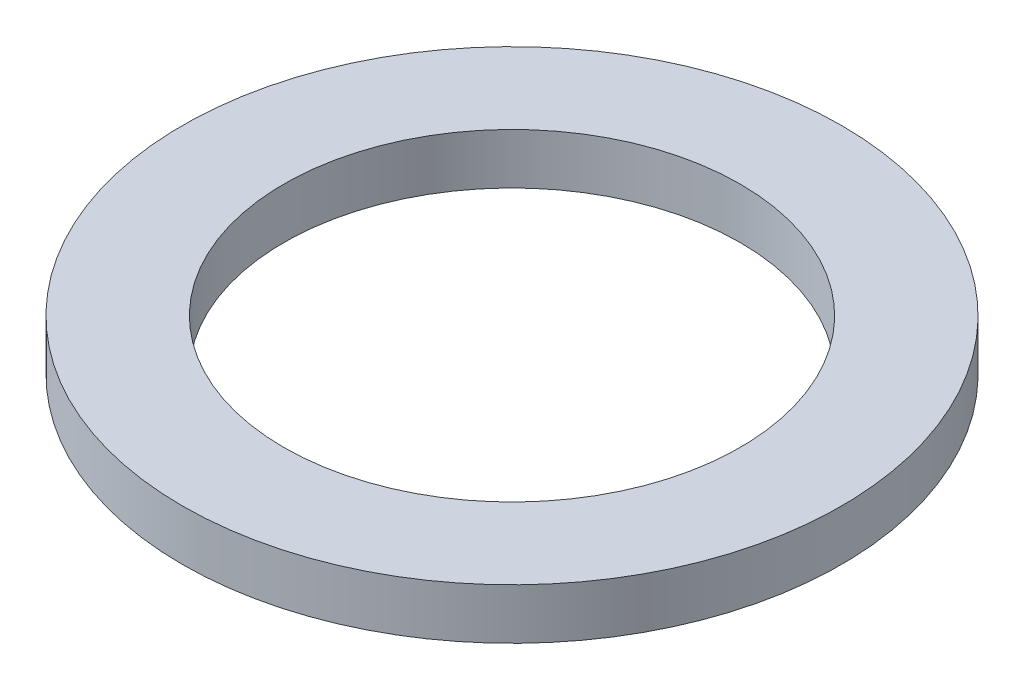
SolidWorks part; units mm, degrees
ref_plane "Plan de face" through (0, 0, 0) normal (0, 0, 1) x (1, 0, 0)
ref_plane "Plan de dessus" through (0, 0, 0) normal (0, 1, 0) x (1, 0, 0)
ref_plane "Plan de droite" through (0, 0, 0) normal (1, 0, 0) x (0, 0, -1)
sketch "Esquisse1" plane through (0, 0, 0) normal (0, 1, 0) x (1, 0, 0)
  circle A0 centre (0, 0) radius 2.25
  circle A1 centre (0, 0) radius 3.25
  dimension "D1" = 4.5
  dimension "D2" = 6.5
extrude "Boss.-Extru.1" add sketch "Esquisse1" along normal blind 0.5
